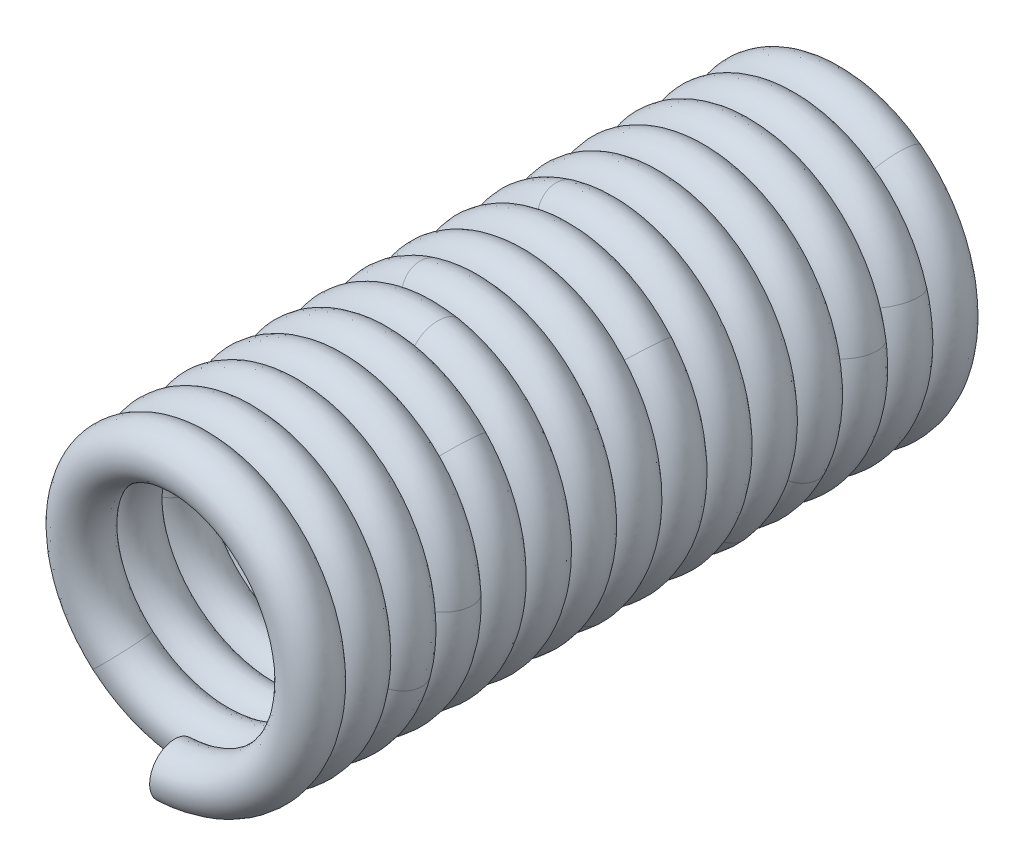
SolidWorks part; units mm, degrees
ref_plane "Front" through (0, 0, 0) normal (0, 0, 1) x (1, 0, 0)
ref_plane "Top" through (0, 0, 0) normal (0, 1, 0) x (1, 0, 0)
ref_plane "Right" through (0, 0, 0) normal (1, 0, 0) x (0, 0, -1)
sketch "Sketch2" plane through (0, 0, 0) normal (0, 0, 1) x (1, 0, 0)
  circle A0 centre (0, 0) radius 6.35
curve "Helix/Spiral1" pitch 2.286 height 34.29 turns 15
sketch "Sketch3" plane through (0, 0, 0) normal (1, 0, 0) x (0, 0, -1)
  circle A0 centre (-34.29, -6.35) radius 1.016
  spline S0 degree 3 poles (0, -6.35) (-0.0473, -6.35) (-0.143, -6.0194) (-0.2857, -4.607) (-0.4286, -2.4933) (-0.5715, 0) (-0.7144, 2.4933) (-0.8572, 4.607) (-1.0001, 6.0194) (-1.143, 6.5153) (-1.2859, 6.0194) (-1.4287, 4.607) (-1.6193, 1.7887) (-1.8098, -1.7887) (-2.0002, -4.607) (-2.1431, -6.0194) (-2.286, -6.5153) (-2.4289, -6.0194) (-2.5717, -4.607) (-2.7623, -1.7887) (-2.9527, 1.7887) (-3.1432, 4.607) (-3.2861, 6.0194) (-3.429, 6.5153) (-3.5719, 6.0194) (-3.7147, 4.607) (-3.9052, 1.7887) (-4.0957, -1.7887) (-4.2862, -4.607) (-4.4291, -6.0194) (-4.572, -6.5153) (-4.7149, -6.0194) (-4.8577, -4.607) (-5.0482, -1.7887) (-5.2387, 1.7887) (-5.4292, 4.607) (-5.5721, 6.0194) (-5.715, 6.5153) (-5.8579, 6.0194) (-6.0007, 4.607) (-6.1912, 1.7887) (-6.3817, -1.7887) (-6.5722, -4.607) (-6.7151, -6.0194) (-6.858, -6.5153) (-7.0009, -6.0194) (-7.1437, -4.607) (-7.3342, -1.7887) (-7.5247, 1.7887) (-7.7152, 4.607) (-7.8581, 6.0194) (-8.001, 6.5153) (-8.1439, 6.0194) (-8.2867, 4.607) (-8.4772, 1.7887) (-8.6677, -1.7887) (-8.8582, -4.607) (-9.0011, -6.0194) (-9.144, -6.5153) (-9.2869, -6.0194) (-9.4297, -4.607) (-9.6203, -1.7887) (-9.8108, 1.7887) (-10.0013, 4.607) (-10.1441, 6.0194) (-10.287, 6.5153) (-10.4299, 6.0194) (-10.5728, 4.607) (-10.7633, 1.7887) (-10.9538, -1.7887) (-11.1443, -4.607) (-11.2871, -6.0194) (-11.43, -6.5153) (-11.5729, -6.0194) (-11.7158, -4.607) (-11.9063, -1.7887) (-12.0968, 1.7887) (-12.2873, 4.607) (-12.4301, 6.0194) (-12.573, 6.5153) (-12.7159, 6.0194) (-12.8588, 4.607) (-13.0493, 1.7887) (-13.2398, -1.7887) (-13.4303, -4.607) (-13.5731, -6.0194) (-13.716, -6.5153) (-13.8589, -6.0194) (-14.0018, -4.607) (-14.1923, -1.7887) (-14.3828, 1.7887) (-14.5733, 4.607) (-14.7161, 6.0194) (-14.859, 6.5153) (-15.0019, 6.0194) (-15.1448, 4.607) (-15.3353, 1.7887) (-15.5258, -1.7887) (-15.7163, -4.607) (-15.8591, -6.0194) (-16.002, -6.5153) (-16.1449, -6.0194) (-16.2878, -4.607) (-16.4783, -1.7887) (-16.6688, 1.7887) (-16.8593, 4.607) (-17.0021, 6.0194) (-17.145, 6.5153) (-17.2879, 6.0194) (-17.4308, 4.607) (-17.6213, 1.7887) (-17.8118, -1.7887) (-18.0023, -4.607) (-18.1451, -6.0194) (-18.288, -6.5153) (-18.4309, -6.0194) (-18.5738, -4.607) (-18.7643, -1.7887) (-18.9548, 1.7887) (-19.1453, 4.607) (-19.2881, 6.0194) (-19.431, 6.5153) (-19.5739, 6.0194) (-19.7168, 4.607) (-19.9073, 1.7887) (-20.0978, -1.7887) (-20.2883, -4.607) (-20.4311, -6.0194) (-20.574, -6.5153) (-20.7169, -6.0194) (-20.8598, -4.607) (-21.0503, -1.7887) (-21.2408, 1.7887) (-21.4313, 4.607) (-21.5741, 6.0194) (-21.717, 6.5153) (-21.8599, 6.0194) (-22.0028, 4.607) (-22.1933, 1.7887) (-22.3838, -1.7887) (-22.5743, -4.607) (-22.7171, -6.0194) (-22.86, -6.5153) (-23.0029, -6.0194) (-23.1458, -4.607) (-23.3363, -1.7887) (-23.5268, 1.7887) (-23.7173, 4.607) (-23.8601, 6.0194) (-24.003, 6.5153) (-24.1459, 6.0194) (-24.2888, 4.607) (-24.4793, 1.7887) (-24.6698, -1.7887) (-24.8603, -4.607) (-25.0031, -6.0194) (-25.146, -6.5153) (-25.2889, -6.0194) (-25.4318, -4.607) (-25.6223, -1.7887) (-25.8128, 1.7887) (-26.0033, 4.607) (-26.1461, 6.0194) (-26.289, 6.5153) (-26.4319, 6.0194) (-26.5748, 4.607) (-26.7653, 1.7887) (-26.9558, -1.7887) (-27.1463, -4.607) (-27.2891, -6.0194) (-27.432, -6.5153) (-27.5749, -6.0194) (-27.7178, -4.607) (-27.9083, -1.7887) (-28.0988, 1.7887) (-28.2893, 4.607) (-28.4321, 6.0194) (-28.575, 6.5153) (-28.7179, 6.0194) (-28.8608, 4.607) (-29.0513, 1.7887) (-29.2418, -1.7887) (-29.4323, -4.607) (-29.5751, -6.0194) (-29.718, -6.5153) (-29.8609, -6.0194) (-30.0038, -4.607) (-30.1943, -1.7887) (-30.3848, 1.7887) (-30.5753, 4.607) (-30.7181, 6.0194) (-30.861, 6.5153) (-31.0039, 6.0194) (-31.1468, 4.607) (-31.3373, 1.7887) (-31.5278, -1.7887) (-31.7183, -4.607) (-31.8611, -6.0194) (-32.004, -6.5153) (-32.1469, -6.0194) (-32.2898, -4.607) (-32.4802, -1.7887) (-32.6707, 1.7887) (-32.8613, 4.607) (-33.0041, 6.0194) (-33.147, 6.5153) (-33.2899, 6.0194) (-33.4328, 4.607) (-33.5756, 2.4933) (-33.7185, 0) (-33.8614, -2.4933) (-34.0043, -4.607) (-34.147, -6.0194) (-34.2427, -6.35) (-34.29, -6.35) knots 0 0 0 0 0.004167 0.008333 0.0125 0.016667 0.020833 0.025 0.029167 0.033333 0.0375 0.041667 0.045833 0.054167 0.058333 0.0625 0.066667 0.070833 0.075 0.079167 0.0875 0.091667 0.095833 0.1 0.104167 0.108333 0.1125 0.120833 0.125 0.129167 0.133333 0.1375 0.141667 0.145833 0.154167 0.158333 0.1625 0.166667 0.170833 0.175 0.179167 0.1875 0.191667 0.195833 0.2 0.204167 0.208333 0.2125 0.220833 0.225 0.229167 0.233333 0.2375 0.241667 0.245833 0.254167 0.258333 0.2625 0.266667 0.270833 0.275 0.279167 0.2875 0.291667 0.295833 0.3 0.304167 0.308333 0.3125 0.320833 0.325 0.329167 0.333333 0.3375 0.341667 0.345833 0.354167 0.358333 0.3625 0.366667 0.370833 0.375 0.379167 0.3875 0.391667 0.395833 0.4 0.404167 0.408333 0.4125 0.420833 0.425 0.429167 0.433333 0.4375 0.441667 0.445833 0.454167 0.458333 0.4625 0.466667 0.470833 0.475 0.479167 0.4875 0.491667 0.495833 0.5 0.504167 0.508333 0.5125 0.520833 0.525 0.529167 0.533333 0.5375 0.541667 0.545833 0.554167 0.558333 0.5625 0.566667 0.570833 0.575 0.579167 0.5875 0.591667 0.595833 0.6 0.604167 0.608333 0.6125 0.620833 0.625 0.629167 0.633333 0.6375 0.641667 0.645833 0.654167 0.658333 0.6625 0.666667 0.670833 0.675 0.679167 0.6875 0.691667 0.695833 0.7 0.704167 0.708333 0.7125 0.720833 0.725 0.729167 0.733333 0.7375 0.741667 0.745833 0.754167 0.758333 0.7625 0.766667 0.770833 0.775 0.779167 0.7875 0.791667 0.795833 0.8 0.804167 0.808333 0.8125 0.820833 0.825 0.829167 0.833333 0.8375 0.841667 0.845833 0.854167 0.858333 0.8625 0.866667 0.870833 0.875 0.879167 0.8875 0.891667 0.895833 0.9 0.904167 0.908333 0.9125 0.920833 0.925 0.929167 0.933333 0.9375 0.941667 0.945833 0.954167 0.958333 0.9625 0.966667 0.970833 0.975 0.979167 0.983333 0.9875 0.991667 0.995833 1 1 1 1 construction
sweep "Sweep1" add path "Helix/Spiral1" circular profile diameter 2.54 parameters "D3"=2.54
